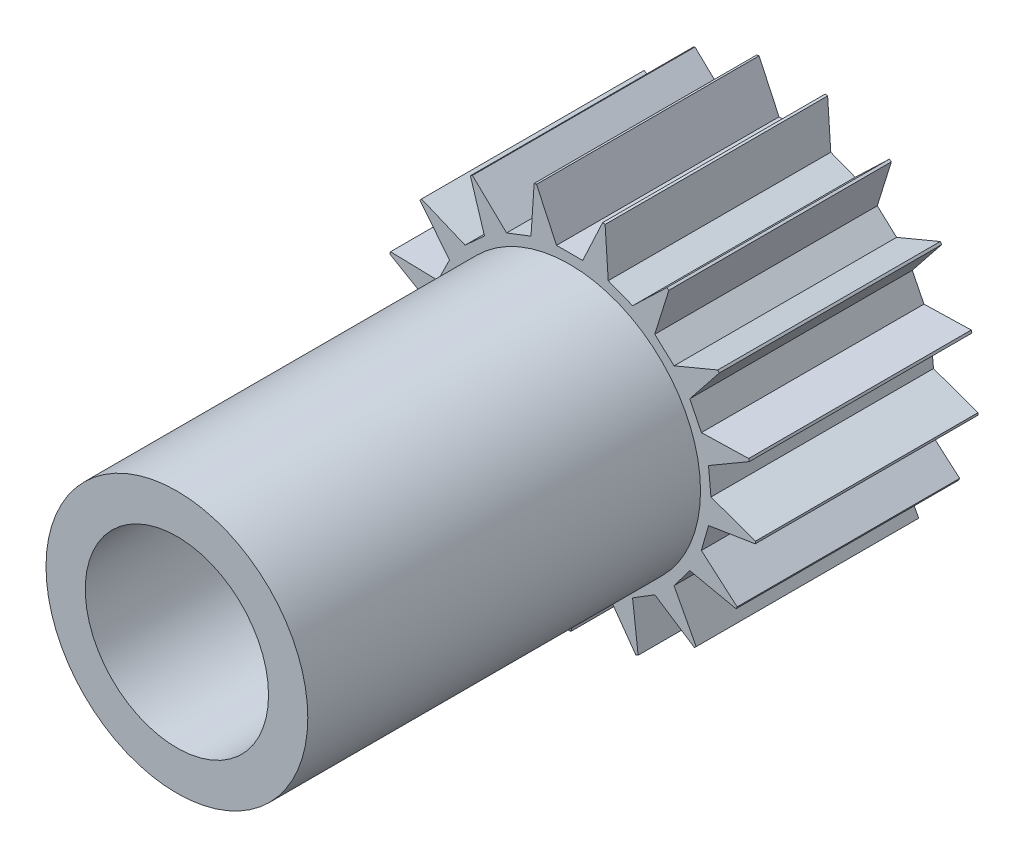
SolidWorks part; units mm, degrees
ref_plane "前视基准面" through (0, 0, 0) normal (0, 0, 1) x (1, 0, 0)
ref_plane "上视基准面" through (0, 0, 0) normal (0, 1, 0) x (1, 0, 0)
ref_plane "右视基准面" through (0, 0, 0) normal (1, 0, 0) x (0, 0, -1)
sketch "草图1" plane through (0, 0, 0) normal (0, 0, 1) x (1, 0, 0)
  circle A0 centre (0, 0) radius 14.25
  dimension "D1" = 28.5
extrude "拉伸1" add sketch "草图1" along normal blind 17
sketch "草图2" plane through (0, 0, 17) normal (0, 0, 1) x (1, 0, 0)
  circle A0 centre (0, 0) radius 10
  dimension "D1" = 20
extrude "拉伸2" add sketch "草图2" along normal blind 30
sketch "草图3" plane through (0, 0, 0) normal (0, 0, -1) x (-1, 0, 0)
  line L0 (2.9509, 10.3853) -> (4.8158, 9.6628)
  line L1 (-1, 10.75) -> (1, 10.75)
  line L2 (2.9509, 10.3853) -> (2.71, 13.9899)
  line L3 (4.8158, 9.6628) -> (7.4223, 12.1644)
  line L4 (6.5032, 8.618) -> (7.9812, 7.2707)
  line L5 (6.5032, 8.618) -> (7.5807, 12.0663)
  line L6 (-1, 10.75) -> (-2.5268, 14.0242)
  line L7 (1, 10.75) -> (2.5268, 14.0242)
  line L8 (7.9812, 7.2707) -> (11.3153, 8.6617)
  line L9 (9.1773, 5.6869) -> (10.0687, 3.8965)
  line L10 (9.1773, 5.6869) -> (11.4277, 8.513)
  line L11 (10.0687, 3.8965) -> (13.6802, 3.9892)
  line L12 (10.6119, 1.9876) -> (10.7964, -0.0038)
  line L13 (10.6119, 1.9876) -> (13.7312, 3.81)
  line L14 (10.7964, -0.0038) -> (14.1975, -1.222)
  line L15 (10.6133, -1.9801) -> (10.066, -3.9037)
  line L16 (10.6133, -1.9801) -> (14.1803, -1.4076)
  line L17 (10.066, -3.9037) -> (12.7973, -6.2682)
  line L18 (9.1813, -5.6803) -> (7.9761, -7.2763)
  line L19 (9.1813, -5.6803) -> (12.7143, -6.435)
  line L20 (7.9761, -7.2763) -> (9.6688, -10.4679)
  line L21 (6.5094, -8.6134) -> (4.8089, -9.6663)
  line L22 (6.5094, -8.6134) -> (9.5311, -10.5934)
  line L23 (4.8089, -9.6663) -> (5.2345, -13.2538)
  line L24 (2.9583, -10.3832) -> (0.9923, -10.7507)
  line L25 (2.9583, -10.3832) -> (5.0607, -13.3211)
  line L26 (0.9923, -10.7507) -> (0.0932, -14.2497)
  line L27 (-0.9923, -10.7507) -> (-2.9583, -10.3832)
  line L28 (-0.9923, -10.7507) -> (-0.0932, -14.2497)
  line L29 (-2.9583, -10.3832) -> (-5.0607, -13.3211)
  line L30 (-4.8089, -9.6663) -> (-6.5094, -8.6134)
  line L31 (-4.8089, -9.6663) -> (-5.2345, -13.2538)
  line L32 (-6.5094, -8.6134) -> (-9.5311, -10.5934)
  line L33 (-7.9761, -7.2763) -> (-9.1813, -5.6803)
  line L34 (-7.9761, -7.2763) -> (-9.6688, -10.4679)
  line L35 (-9.1813, -5.6803) -> (-12.7143, -6.435)
  line L36 (-10.066, -3.9037) -> (-10.6133, -1.9801)
  line L37 (-10.066, -3.9037) -> (-12.7973, -6.2682)
  line L38 (-10.6133, -1.9801) -> (-14.1803, -1.4076)
  line L39 (-10.7964, -0.0038) -> (-10.6119, 1.9876)
  line L40 (-10.7964, -0.0038) -> (-14.1975, -1.222)
  line L41 (-10.6119, 1.9876) -> (-13.7312, 3.81)
  line L42 (-10.0687, 3.8965) -> (-9.1773, 5.6869)
  line L43 (-10.0687, 3.8965) -> (-13.6802, 3.9892)
  line L44 (-9.1773, 5.6869) -> (-11.4277, 8.513)
  line L45 (-7.9812, 7.2707) -> (-6.5032, 8.618)
  line L46 (-7.9812, 7.2707) -> (-11.3153, 8.6617)
  line L47 (-6.5032, 8.618) -> (-7.5807, 12.0663)
  line L48 (-4.8158, 9.6628) -> (-2.9509, 10.3853)
  line L49 (-4.8158, 9.6628) -> (-7.4223, 12.1644)
  line L50 (-2.9509, 10.3853) -> (-2.71, 13.9899)
  arc A0 (2.5268, 14.0242) -> (-2.5268, 14.0242) centre (0, 0) ccw
  arc A1 (7.4223, 12.1644) -> (2.71, 13.9899) centre (0, 0) ccw
  arc A2 (11.3153, 8.6617) -> (7.5807, 12.0663) centre (0, 0) ccw
  arc A3 (13.6802, 3.9892) -> (11.4277, 8.513) centre (0, 0) ccw
  arc A4 (14.1975, -1.222) -> (13.7312, 3.81) centre (0, 0) ccw
  arc A5 (12.7973, -6.2682) -> (14.1803, -1.4076) centre (0, 0) ccw
  arc A6 (9.6688, -10.4679) -> (12.7143, -6.435) centre (0, 0) ccw
  arc A7 (5.2345, -13.2538) -> (9.5311, -10.5934) centre (0, 0) ccw
  arc A8 (0.0932, -14.2497) -> (5.0607, -13.3211) centre (0, 0) ccw
  arc A9 (-5.0607, -13.3211) -> (-0.0932, -14.2497) centre (0, 0) ccw
  arc A10 (-9.5311, -10.5934) -> (-5.2345, -13.2538) centre (0, 0) ccw
  arc A11 (-12.7143, -6.435) -> (-9.6688, -10.4679) centre (0, 0) ccw
  arc A12 (-14.1803, -1.4076) -> (-12.7973, -6.2682) centre (0, 0) ccw
  arc A13 (-13.7312, 3.81) -> (-14.1975, -1.222) centre (0, 0) ccw
  arc A14 (-11.4277, 8.513) -> (-13.6802, 3.9892) centre (0, 0) ccw
  arc A15 (-7.5807, 12.0663) -> (-11.3153, 8.6617) centre (0, 0) ccw
  arc A16 (-2.71, 13.9899) -> (-7.4223, 12.1644) centre (0, 0) ccw
extrude "切除-拉伸1" cut sketch "草图3" against normal through all
sketch "草图4" plane through (0, 0, 47) normal (0, 0, 1) x (1, 0, 0)
  circle A0 centre (0, 0) radius 7
extrude "切除-拉伸2" cut sketch "草图4" against normal through all
